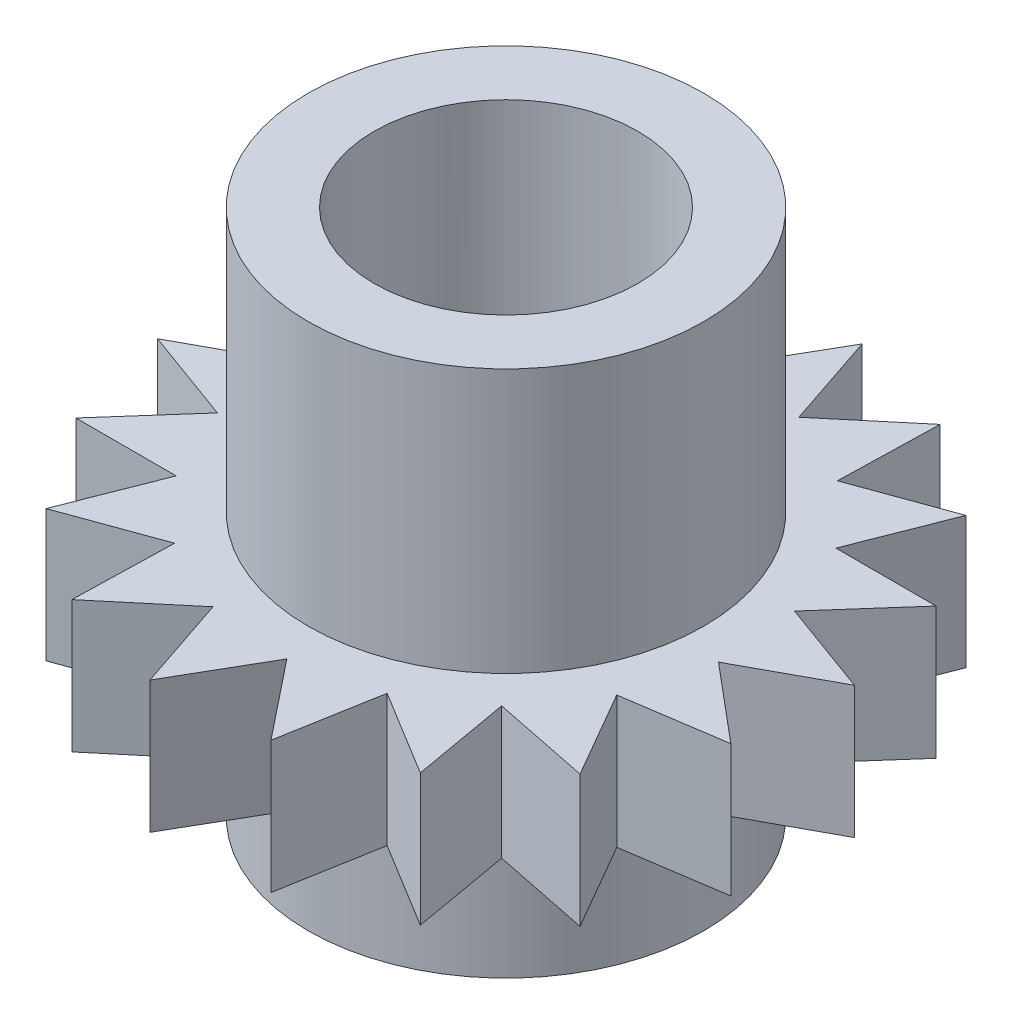
SolidWorks part; units mm, degrees
ref_plane "Front Plane" through (0, 0, 0) normal (0, 0, 1) x (1, 0, 0)
ref_plane "Top Plane" through (0, 0, 0) normal (0, 1, 0) x (1, 0, 0)
ref_plane "Right Plane" through (0, 0, 0) normal (1, 0, 0) x (0, 0, -1)
sketch "Sketch1" plane through (0, 0, 0) normal (0, 1, 0) x (1, 0, 0)
  line L0 (-0.669, 8.9751) -> (1.2322, 12.2653)
  line L1 (1.2322, 12.2653) -> (2.441, 8.6627)
  line L2 (5.3529, 11.1041) -> (5.2566, 7.3054)
  line L3 (2.441, 8.6627) -> (5.3529, 11.1041)
  line L4 (8.8279, 8.6037) -> (7.4382, 5.0669)
  line L5 (5.2566, 7.3054) -> (8.8279, 8.6037)
  line L6 (11.2382, 5.0655) -> (8.7226, 2.2174)
  line L7 (7.4382, 5.0669) -> (11.2382, 5.0655)
  line L8 (12.2929, 0.9163) -> (8.9549, -0.8996)
  line L9 (8.7226, 2.2174) -> (12.2929, 0.9163)
  line L10 (11.865, -3.3433) -> (8.1072, -3.9082)
  line L11 (8.9549, -0.8996) -> (11.865, -3.3433)
  line L12 (10.0059, -7.1998) -> (6.2816, -6.4453)
  line L13 (8.1072, -3.9082) -> (10.0059, -7.1998)
  line L14 (6.94, -10.1878) -> (3.6983, -8.205)
  line L15 (6.2816, -6.4453) -> (6.94, -10.1878)
  line L16 (3.0371, -11.947) -> (0.669, -8.9751)
  line L17 (3.6983, -8.205) -> (3.0371, -11.947)
  line L18 (-1.2322, -12.2653) -> (-2.441, -8.6627)
  line L19 (0.669, -8.9751) -> (-1.2322, -12.2653)
  line L20 (-5.3529, -11.1041) -> (-5.2566, -7.3054)
  line L21 (-2.441, -8.6627) -> (-5.3529, -11.1041)
  line L22 (-8.8279, -8.6037) -> (-7.4382, -5.0669)
  line L23 (-5.2566, -7.3054) -> (-8.8279, -8.6037)
  line L24 (-11.2382, -5.0655) -> (-8.7226, -2.2174)
  line L25 (-7.4382, -5.0669) -> (-11.2382, -5.0655)
  line L26 (-12.2929, -0.9163) -> (-8.9549, 0.8996)
  line L27 (-8.7226, -2.2174) -> (-12.2929, -0.9163)
  line L28 (-11.865, 3.3433) -> (-8.1072, 3.9082)
  line L29 (-8.9549, 0.8996) -> (-11.865, 3.3433)
  line L30 (-10.0059, 7.1998) -> (-6.2816, 6.4453)
  line L31 (-8.1072, 3.9082) -> (-10.0059, 7.1998)
  line L32 (-6.94, 10.1878) -> (-3.6983, 8.205)
  line L33 (-6.2816, 6.4453) -> (-6.94, 10.1878)
  line L34 (-3.0371, 11.947) -> (-0.669, 8.9751)
  line L35 (-3.6983, 8.205) -> (-3.0371, 11.947)
  circle A0 centre (0, 0) radius 9
  point P5 (2.3448, 8.6627)
  point P60 (0, 0)
  dimension "D1" = 18
  dimension "D2" = 3.8
extrude "Boss-Extrude1" add sketch "Sketch1" along normal blind 5 contours A0 | L20 L23 L22 L25 L24 L27 L26 L29 L28 L31 L30 L33 L32 L35 L34 L0 L1 L3 L2 L5 L4 L7 L6 L9 L8 L11 L10 L13 L12 L15 L14 L17 L16 L19 L18 L21
sketch "Sketch2" plane through (0, 5, 0) normal (0, 1, 0) x (1, 0, 0)
  circle A0 centre (0, 0) radius 7.5
  dimension "D1" = 15
extrude "Boss-Extrude2" add sketch "Sketch2" along normal mid plane 20
sketch "Sketch3" plane through (0, 15, 0) normal (0, 1, 0) x (1, 0, 0)
  circle A0 centre (0, 0) radius 5
  dimension "D1" = 10
extrude "Cut-Extrude1" cut sketch "Sketch3" against normal blind 20
sketch "Sketch4" plane through (0, 5, 0) normal (0, 1, 0) x (1, 0, 0)
  line L1 (-2, 6) -> (2, 6)
  line L2 (-2, 6) -> (-2, 4)
  line L3 (-2, 4) -> (2, 4)
  line L4 (2, 6) -> (2, 4)
  line L5 (-2, 6) -> (2, 4) construction
  line L6 (-2, 4) -> (2, 6) construction
  circle A0 centre (0, 0) radius 5 construction
  point P0 (0, 5)
  dimension "D1" = 4
  dimension "D2" = 2
extrude "Boss-Extrude3" add sketch "Sketch4" against normal blind 10
